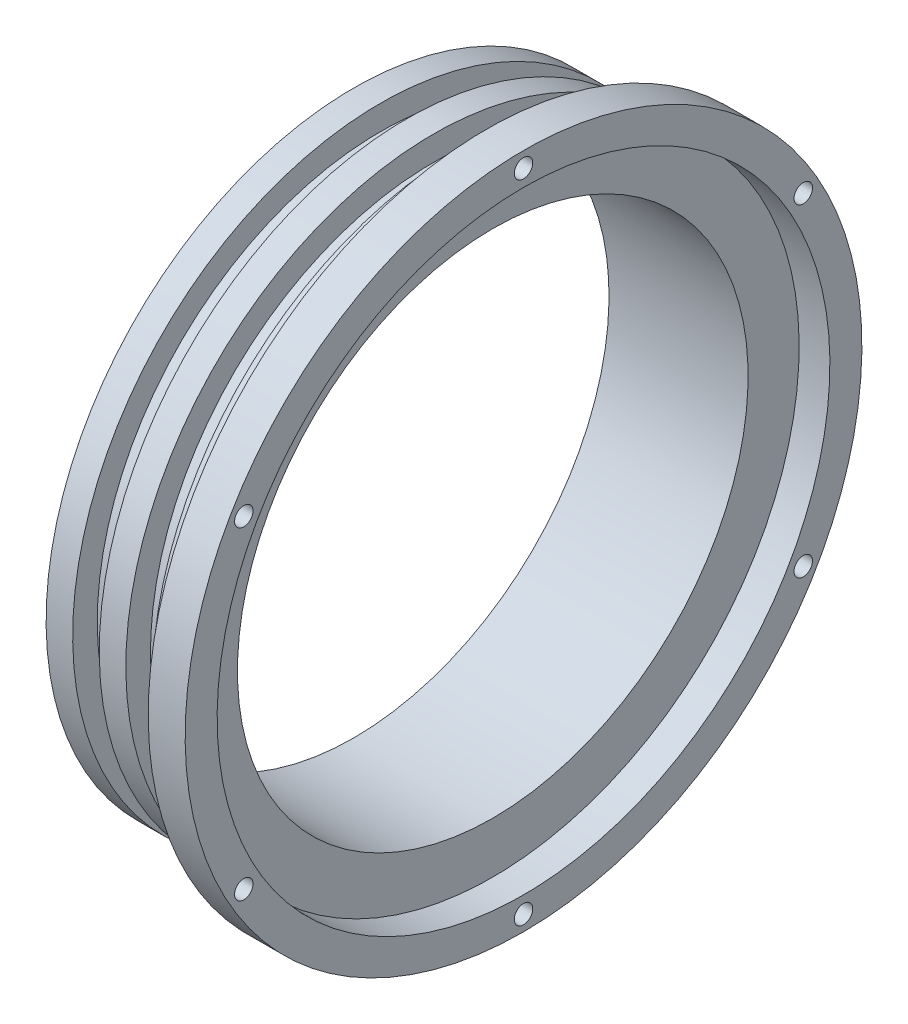
SolidWorks part; units mm, degrees
ref_plane "前视基准面" through (0, 0, 0) normal (0, 0, 1) x (1, 0, 0)
ref_plane "上视基准面" through (0, 0, 0) normal (0, 1, 0) x (1, 0, 0)
ref_plane "右视基准面" through (0, 0, 0) normal (1, 0, 0) x (0, 0, -1)
other "Configuration Table"
sketch "草图1" plane through (0, 0, 0) normal (0, 0, 1) x (1, 0, 0)
  line L0 (27.6, 0) -> (131.04, 0) construction
  line L1 (0, 41.5) -> (0, 50)
  line L2 (0, 50) -> (4.32, 50)
  line L3 (4.32, 50) -> (4.32, 46)
  line L4 (4.32, 46) -> (8.64, 46)
  line L5 (8.64, 46) -> (8.64, 50)
  line L6 (8.64, 50) -> (12.96, 50)
  line L7 (12.96, 50) -> (12.96, 46)
  line L8 (12.96, 46) -> (17.28, 46)
  line L9 (17.28, 46) -> (17.28, 50)
  line L10 (17.28, 50) -> (21.6, 50)
  line L11 (21.6, 50) -> (21.6, 55)
  line L12 (21.6, 55) -> (27.6, 55)
  line L13 (27.6, 55) -> (27.6, 41.5)
  line L15 (0, 41.5) -> (27.6, 41.5)
  dimension "D1" = 6
  dimension "D2" = 110
  dimension "D3" = 100
  dimension "D4" = 27.6
  dimension "D5" = 4.32
  dimension "D6" = 4.32
  dimension "D7" = 4.32
  dimension "D8" = 4.32
  dimension "D9" = 4
  dimension "D10" = 4
  dimension "D11" = 4
  dimension "D12" = 4
revolve "旋转1" add sketch "草图1" angle 360 about L0
sketch "草图2" plane through (0, 0, 0) normal (-1, 0, 0) x (0, 0, 1)
  circle A0 centre (0, 0) radius 44
  circle A1 centre (0, 44) radius 1.5
  dimension "D1" = 88
  dimension "D2" = 3
extrude "切除-拉伸1" cut sketch "草图2" against normal blind 6 contours A0 A1 | A0 A1
pattern_circular "阵列(圆周)1" count 6 over 360 about axis through (0, 0, 0) along (1, 0, 0) of "切除-拉伸1"
sketch "草图3" plane through (21.6, 0, 0) normal (-1, 0, 0) x (0, 0, 1)
  circle A0 centre (0, 0) radius 52.5
  circle A1 centre (0, 52.5) radius 1.5
  dimension "D1" = 105
  dimension "D2" = 3
extrude "切除-拉伸2" cut sketch "草图3" against normal through all both and the other way through all contours A0 A1 | A0 A1
pattern_circular "阵列(圆周)2" count 6 over 360 about axis through (0, 0, 0) along (1, 0, 0) of "切除-拉伸2"
sketch "草图4" plane through (27.6, 0, 0) normal (1, 0, 0) x (0, 0, -1)
  circle A0 centre (0, 0) radius 45.5
  circle A1 centre (0, 0) radius 49.8
  dimension "D1" = 91
  dimension "D2" = 99.6
extrude "切除-拉伸3" cut sketch "草图4" against normal blind 5 contours A1
